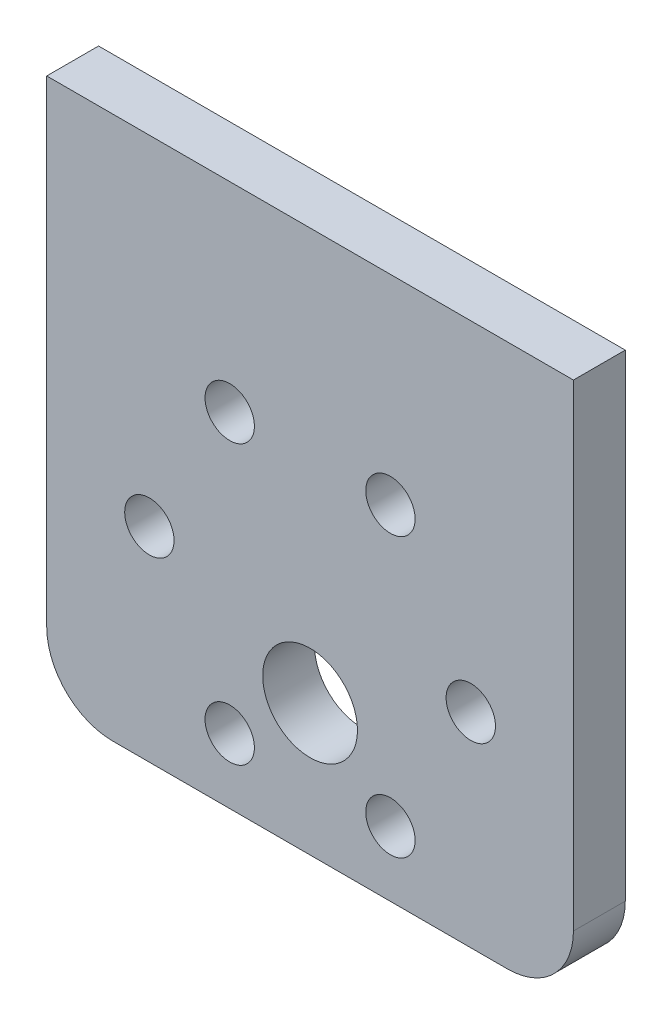
SolidWorks part; units mm, degrees
material "Oak"
ref_plane "Front Plane" through (0, 0, 0) normal (0, 0, 1) x (1, 0, 0)
ref_plane "Top Plane" through (0, 0, 0) normal (0, 1, 0) x (1, 0, 0)
ref_plane "Right Plane" through (0, 0, 0) normal (1, 0, 0) x (0, 0, -1)
sketch "Sketch1" plane through (0, 0, 0) normal (0, 0, 1) x (1, 0, 0)
  line L1 (-25.4, -26.1874) -> (25.4, -26.1874)
  line L2 (-25.4, -26.1874) -> (-25.4, 26.1874)
  line L3 (-25.4, 26.1874) -> (25.4, 26.1874)
  line L4 (25.4, -26.1874) -> (25.4, 26.1874)
  line L5 (-25.4, -26.1874) -> (25.4, 26.1874) construction
  line L6 (-25.4, 26.1874) -> (25.4, -26.1874) construction
  point P0 (0, 0)
  dimension "D1" = 52.3748
  dimension "D2" = 50.8
extrude "Boss-Extrude1" add sketch "Sketch1" along normal mid plane 5
hole_wizard "1/2 (0.5) Diameter Hole1" positions "Sketch2" profile "Sketch3" hole size "1/2" standard "ANSI Inch" end condition through all
sketch "Sketch2" plane through (0, 0, 2.5) normal (0, 0, 1) x (1, 0, 0)
  line L0 (-25.4, -26.1874) -> (25.4, -26.1874) construction
  point P8 (0, -13.4874)
  dimension "D1" = 12.7
sketch "Sketch3" plane through (0, -13.4874, 2.5) normal (1, 0, 0) x (0, -1, 0)
  line L0 (0, 0) -> (0, 5)
  line L1 (0, 5) -> (4.572, 5)
  line L2 (4.572, 5) -> (4.572, 0)
  line L5 (4.572, 0) -> (0, 0)
  line L11 (0, -6.35) -> (0, 107.95) construction
  dimension "Thru Hole Dia." = 9.144
  dimension "Thru Hole Depth" = 5
hole_wizard "3/16 (0.1875) Diameter Hole1" positions "Sketch4" profile "Sketch5" hole size "3/16" standard "ANSI Inch" end condition through all
sketch "Sketch4" plane through (0, 0, -2.5) normal (0, 0, -1) x (-1, 0, 0)
  point P17 (15.5, -6.4874)
  point P20 (7.75, 6.936)
  point P23 (-7.75, 6.936)
  point P26 (-15.5, -6.4874)
  point P31 (7.75, -19.9108)
  point P34 (-7.75, -19.9108)
sketch "Sketch5" plane through (-15.5, -6.4874, -2.5) normal (1, 0, 0) x (0, 1, 0)
  line L0 (0, 0) -> (0, 5)
  line L1 (0, 5) -> (2.3812, 5)
  line L2 (2.3812, 5) -> (2.3812, 0)
  line L5 (2.3812, 0) -> (0, 0)
  line L11 (0, -6.35) -> (0, 107.95) construction
  dimension "Thru Hole Dia." = 4.7625
  dimension "Thru Hole Depth" = 5
fillet "Fillet1" radius 6.35 2 edges at (25.4, -26.1874, 0) (-25.4, -26.1874, 0)
